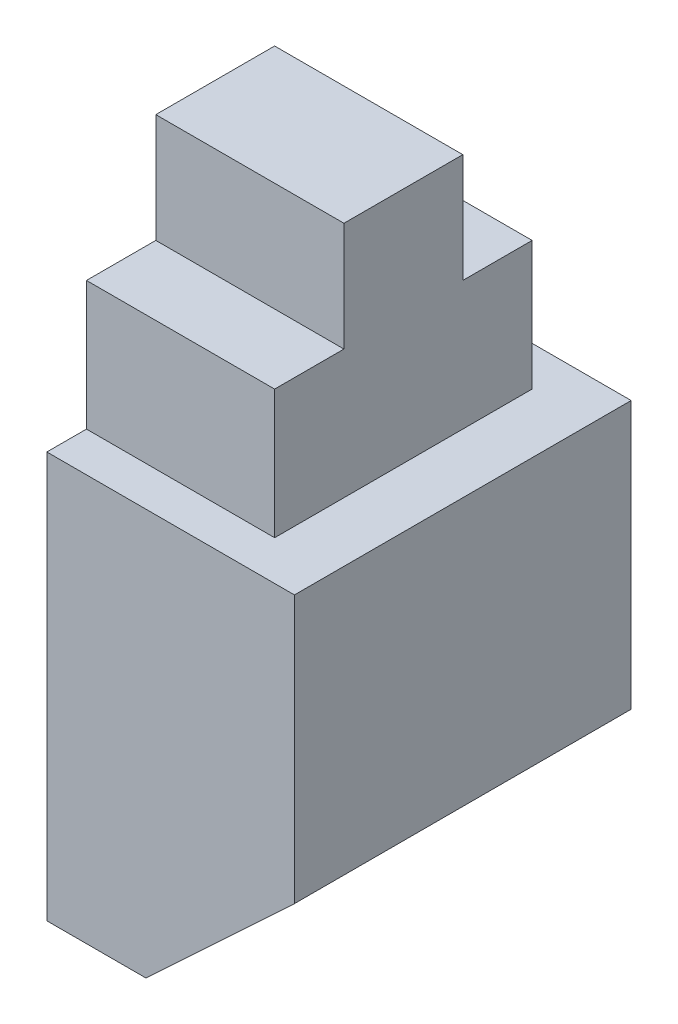
SolidWorks part; units mm, degrees
ref_plane "Front Plane" through (0, 0, 0) normal (0, 0, 1) x (1, 0, 0)
ref_plane "Top Plane" through (0, 0, 0) normal (0, 1, 0) x (1, 0, 0)
ref_plane "Right Plane" through (0, 0, 0) normal (1, 0, 0) x (0, 0, -1)
sketch "Sketch1" plane through (0, 0, 0) normal (0, 0, 1) x (1, 0, 0)
  line L0 (-12.5, 20.5) -> (-12.5, -20.5)
  line L1 (-12.5, -20.5) -> (-2.5, -20.5)
  line L2 (-2.5, -20.5) -> (12.5, -6.5)
  line L3 (12.5, -6.5) -> (12.5, 20.5)
  line L4 (12.5, 20.5) -> (-12.5, 20.5)
  point P2 (-12.5, 0)
  point P6 (0, 20.5)
  dimension "D1" = 25
  dimension "D2" = 41
  dimension "D3" = 10
  dimension "D4" = 27
extrude "Boss-Extrude1" add sketch "Sketch1" against normal blind 34
sketch "Sketch2" plane through (-12.5, 0, 0) normal (-1, 0, 0) x (0, 0, 1)
  line L0 (-30, 20.5) -> (-30, 33.5)
  line L2 (-30, 33.5) -> (-23, 33.5)
  line L3 (-23, 33.5) -> (-23, 44.5)
  line L4 (-23, 44.5) -> (-11, 44.5)
  line L5 (-11, 44.5) -> (-11, 33.5)
  line L6 (-11, 33.5) -> (-4, 33.5)
  line L7 (-4, 33.5) -> (-4, 20.5)
  line L8 (-4, 20.5) -> (-30, 20.5)
  line L9 (-34, 20.5) -> (0, 20.5) construction
  point P2 (-17, 20.5)
  point P11 (-17, 20.5)
  dimension "D1" = 13
  dimension "D2" = 12
  dimension "D3" = 26
  dimension "D4" = 11
  dimension "D5" = 7
extrude "Boss-Extrude2" add sketch "Sketch2" against normal blind 19
sketch "Sketch3" plane through (-12.5, 0, 0) normal (-1, 0, 0) x (0, 0, 1)
  line L0 (-34, -20.5) -> (0, -20.5) construction
  line L1 (-26, -12.5) -> (-8, -12.5)
  line L2 (-26, -12.5) -> (-26, -20.5)
  line L3 (-26, -20.5) -> (-8, -20.5)
  line L4 (-8, -12.5) -> (-8, -20.5)
  line L5 (-26, -12.5) -> (-8, -20.5) construction
  line L6 (-26, -20.5) -> (-8, -12.5) construction
  point P0 (-17, -16.5)
  point P5 (-17, -20.5)
  point P8 (-17, -20.5)
  dimension "D1" = 18
  dimension "D2" = 8
extrude "Cut-Extrude1" cut sketch "Sketch3" against normal through all
